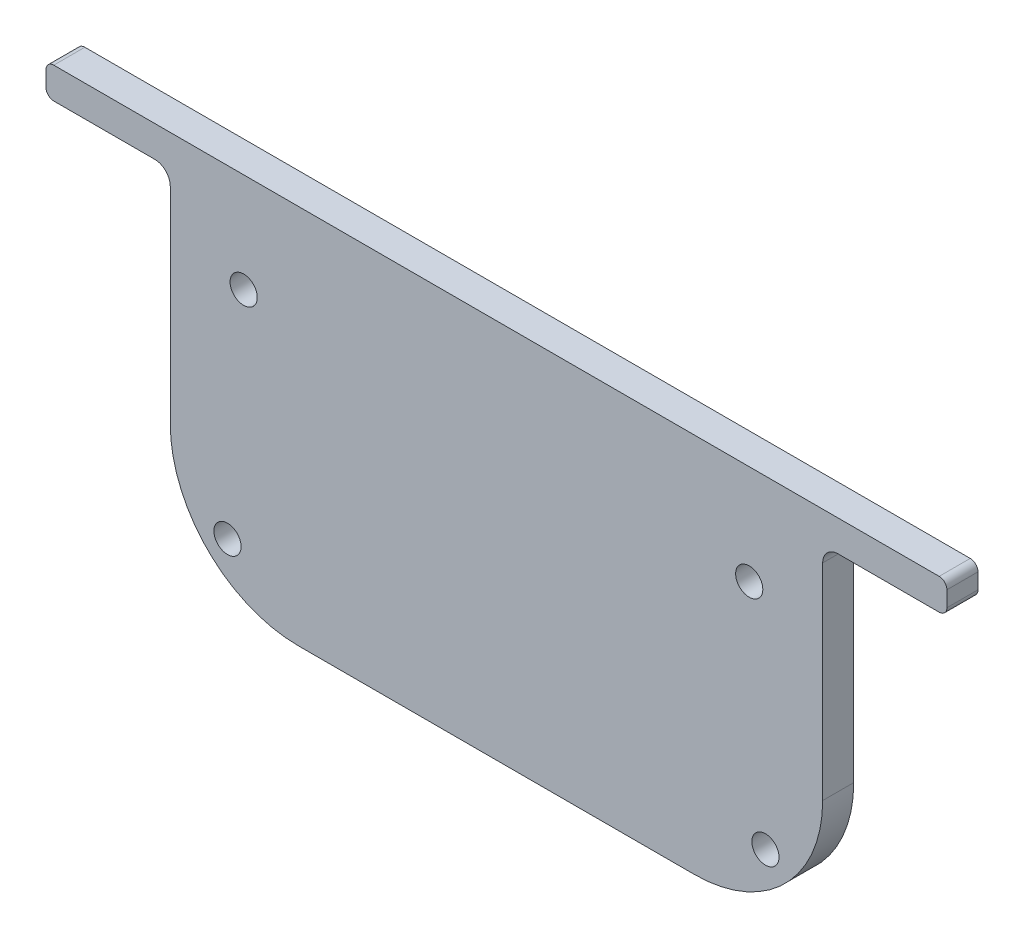
SolidWorks part; units mm, degrees
ref_plane "Front Plane" through (0, 0, 0) normal (0, 0, 1) x (1, 0, 0)
ref_plane "Top Plane" through (0, 0, 0) normal (0, 1, 0) x (1, 0, 0)
ref_plane "Right Plane" through (0, 0, 0) normal (1, 0, 0) x (0, 0, -1)
sketch "Sketch1" plane through (0, 0, 0) normal (0, 0, 1) x (1, 0, 0)
  line L0 (163.5801, 21.2957) -> (163.5801, 47.7957) construction
  line L1 (96.0801, 4.7957) -> (147.0801, 4.7957) construction
  line L2 (79.5801, 47.7957) -> (79.5801, 21.2957) construction
  line L3 (178.5801, 53.7957) -> (64.5801, 53.7957) construction
  line L4 (163.5801, 21.2957) -> (163.5801, 47.7957)
  line L5 (96.0801, 4.7957) -> (147.0801, 4.7957)
  line L6 (79.5801, 47.7957) -> (79.5801, 21.2957)
  line L7 (178.5801, 53.7957) -> (64.5801, 53.7957)
  line L8 (63.5801, 50.7957) -> (63.5801, 52.7957) construction
  line L9 (77.5801, 49.7957) -> (64.5801, 49.7957) construction
  line L10 (179.5801, 50.7957) -> (179.5801, 52.7957) construction
  line L11 (165.5801, 49.7957) -> (178.5801, 49.7957) construction
  line L12 (63.5801, 50.7957) -> (63.5801, 52.7957)
  line L13 (77.5801, 49.7957) -> (64.5801, 49.7957)
  line L14 (179.5801, 50.7957) -> (179.5801, 52.7957)
  line L15 (165.5801, 49.7957) -> (178.5801, 49.7957)
  circle A0 centre (154.1226, 40.988) radius 1.25 construction
  circle A1 centre (156.2137, 12.162) radius 1.25 construction
  circle A2 centre (86.9465, 12.162) radius 1.25 construction
  circle A3 centre (89.0301, 40.988) radius 1.25 construction
  arc A5 (147.0801, 4.7957) -> (163.5801, 21.2957) centre (147.0801, 21.2957) ccw construction
  arc A6 (79.5801, 21.2957) -> (96.0801, 4.7957) centre (96.0801, 21.2957) ccw construction
  circle A8 centre (154.1226, 40.988) radius 1.25 construction
  circle A9 centre (156.2137, 12.162) radius 1.25 construction
  circle A10 centre (86.9465, 12.162) radius 1.25 construction
  circle A11 centre (89.0301, 40.988) radius 1.25 construction
  arc A12 (64.5801, 53.7957) -> (63.5801, 52.7957) centre (64.5801, 52.7957) ccw construction
  arc A13 (147.0801, 4.7957) -> (163.5801, 21.2957) centre (147.0801, 21.2957) ccw
  arc A14 (79.5801, 21.2957) -> (96.0801, 4.7957) centre (96.0801, 21.2957) ccw
  arc A15 (63.5801, 50.7957) -> (64.5801, 49.7957) centre (64.5801, 50.7957) ccw construction
  circle A16 centre (89.0301, 40.988) radius 1.75
  circle A17 centre (86.9465, 12.162) radius 1.75
  circle A18 centre (154.1226, 40.988) radius 1.75
  circle A19 centre (156.2137, 12.162) radius 1.75
  arc A20 (79.5801, 47.7957) -> (77.5801, 49.7957) centre (77.5801, 47.7957) ccw construction
  arc A21 (179.5801, 52.7957) -> (178.5801, 53.7957) centre (178.5801, 52.7957) ccw construction
  arc A22 (178.5801, 49.7957) -> (179.5801, 50.7957) centre (178.5801, 50.7957) ccw construction
  arc A23 (165.5801, 49.7957) -> (163.5801, 47.7957) centre (165.5801, 47.7957) ccw construction
  arc A24 (64.5801, 53.7957) -> (63.5801, 52.7957) centre (64.5801, 52.7957) ccw
  arc A25 (63.5801, 50.7957) -> (64.5801, 49.7957) centre (64.5801, 50.7957) ccw
  arc A26 (79.5801, 47.7957) -> (77.5801, 49.7957) centre (77.5801, 47.7957) ccw
  arc A27 (179.5801, 52.7957) -> (178.5801, 53.7957) centre (178.5801, 52.7957) ccw
  arc A28 (178.5801, 49.7957) -> (179.5801, 50.7957) centre (178.5801, 50.7957) ccw
  arc A29 (165.5801, 49.7957) -> (163.5801, 47.7957) centre (165.5801, 47.7957) ccw
  dimension "D1" = 0.5
extrude "Boss-Extrude1" add sketch "Sketch1" along normal blind 4
